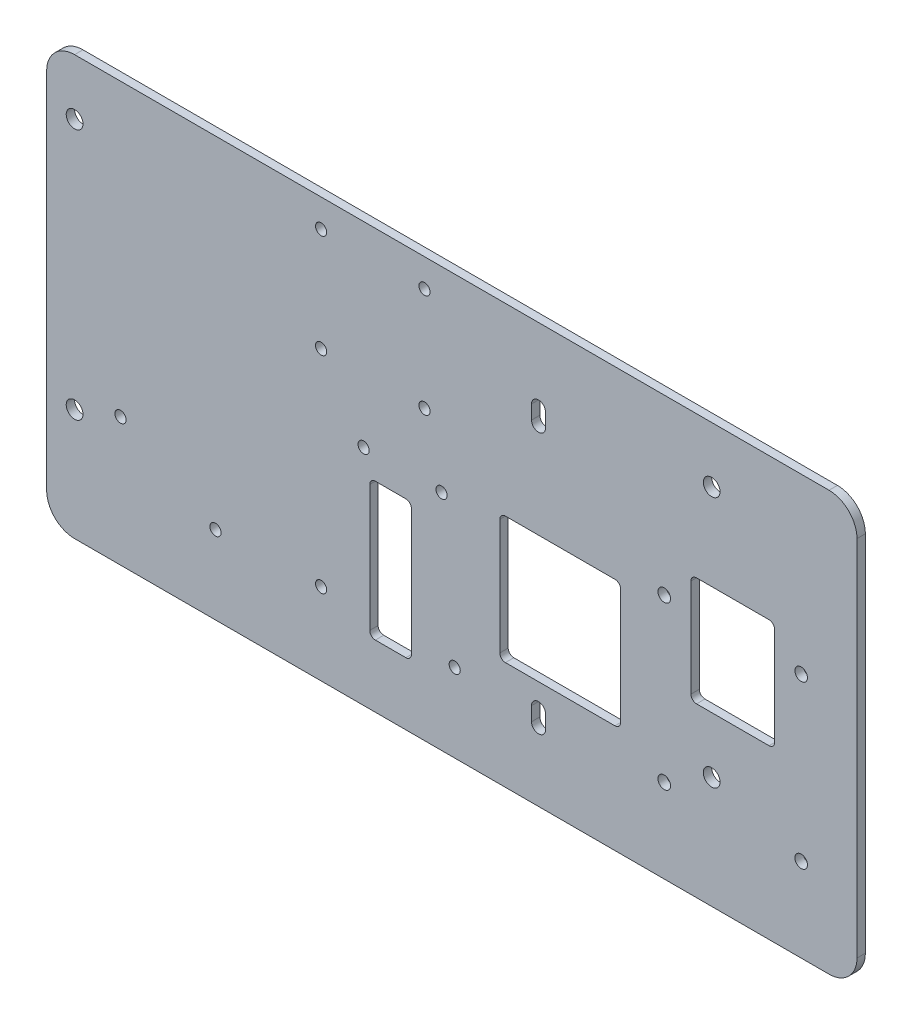
SolidWorks part; units mm, degrees
ref_plane "정면" through (0, 0, 0) normal (0, 0, 1) x (1, 0, 0)
ref_plane "윗면" through (0, 0, 0) normal (0, 1, 0) x (1, 0, 0)
ref_plane "우측면" through (0, 0, 0) normal (1, 0, 0) x (0, 0, -1)
sketch "스케치1" plane through (0, 0, 0) normal (0, 0, 1) x (1, 0, 0)
  line L0 (-145, 65) -> (145, 65) construction
  line L1 (-145, 75) -> (145, 75)
  line L2 (-145, 75) -> (-145, -75)
  line L3 (-145, -75) -> (145, -75)
  line L4 (145, 75) -> (145, -75)
  line L5 (-145, 75) -> (145, -75) construction
  line L6 (-145, -75) -> (145, 75) construction
  line L7 (145, 65) -> (145, 55) construction
  line L8 (145, 55) -> (-145, 55) construction
  line L9 (-145, -65) -> (145, -65) construction
  line L10 (-145, -75) -> (-140, -75)
  line L11 (-145, -75) -> (-145, -55)
  line L12 (-145, -55) -> (-140, -55)
  line L13 (-140, -75) -> (-140, -55)
  line L18 (-125, 55) -> (-145, 25) construction
  line L19 (125, 55) -> (145, 25) construction
  line L20 (31.0272, 46) -> (31.0272, -50) construction
  line L21 (76.0272, 13) -> (125.0272, 13) construction
  line L22 (76.0272, 13) -> (76.0272, -45) construction
  line L23 (76.0272, -45) -> (125.0272, -45) construction
  line L24 (125.0272, 13) -> (125.0272, -45) construction
  line L25 (76.0272, 13) -> (125.0272, -45) construction
  line L26 (76.0272, -45) -> (125.0272, 13) construction
  line L27 (125.0272, -45) -> (161.0272, -45) construction
  line L28 (125.0272, -45) -> (125.0272, 13) construction
  line L29 (125.0272, 13) -> (161.0272, 13) construction
  line L30 (161.0272, -45) -> (161.0272, 13) construction
  line L41 (26.0272, 46) -> (62.0272, 46) construction
  line L42 (26.0272, 46) -> (26.0272, -50) construction
  line L43 (26.0272, -50) -> (62.0272, -50) construction
  line L44 (62.0272, 46) -> (62.0272, -50) construction
  line L45 (26.0272, 46) -> (62.0272, -50) construction
  line L46 (26.0272, -50) -> (62.0272, 46) construction
  line L47 (31.0272, 43.5) -> (31.0272, 48.5) construction
  line L48 (28.5272, 43.5) -> (28.5272, 48.5)
  line L49 (33.5272, 43.5) -> (33.5272, 48.5)
  line L50 (31.0272, -45) -> (31.0272, -50) construction
  line L51 (33.5272, -45) -> (33.5272, -50)
  line L52 (28.5272, -45) -> (28.5272, -50)
  line L53 (-118.5728, -26) -> (-118.5728, -50) construction
  line L54 (-128.3728, -50) -> (-74.7728, -50) construction
  line L55 (-128.3728, -50) -> (-128.3728, -26) construction
  line L56 (-128.3728, -26) -> (-74.7728, -26) construction
  line L57 (-74.7728, -50) -> (-74.7728, -26) construction
  line L58 (-128.3728, -50) -> (-74.7728, -26) construction
  line L59 (-128.3728, -26) -> (-74.7728, -50) construction
  line L60 (-84.5728, -26) -> (-84.5728, -50) construction
  line L61 (-128.3728, -29) -> (-74.7728, -29) construction
  line L62 (-74.7728, -47) -> (-128.3728, -47) construction
  line L63 (-46.7728, 5) -> (1.0272, 5) construction
  line L64 (-46.7728, 5) -> (-46.7728, -46.9) construction
  line L65 (-46.7728, -46.9) -> (1.0272, -46.9) construction
  line L66 (1.0272, 5) -> (1.0272, -46.9) construction
  line L67 (-46.7728, 5) -> (1.0272, -46.9) construction
  line L68 (-46.7728, -46.9) -> (1.0272, 5) construction
  line L69 (1.0272, -46.9) -> (-46.7728, -46.9) construction
  line L70 (1.0272, -46.9) -> (1.0272, -65) construction
  line L71 (1.0272, -65) -> (-46.7728, -65) construction
  line L72 (-46.7728, -46.9) -> (-46.7728, -65) construction
  line L73 (-9.7728, 65) -> (-46.7728, 65) construction
  line L74 (-9.7728, 65) -> (-9.7728, 28) construction
  line L75 (-9.7728, 28) -> (-46.7728, 28) construction
  line L76 (-46.7728, 65) -> (-46.7728, 28) construction
  line L77 (-9.7728, 65) -> (-46.7728, 28) construction
  line L78 (-9.7728, 28) -> (-46.7728, 65) construction
  circle A2 centre (76.0272, 13) radius 2.25
  circle A3 centre (76.0272, -45) radius 2.25
  circle A4 centre (125.0272, -45) radius 2.25
  circle A5 centre (125.0272, 13) radius 2.25
  arc A10 (28.5272, 43.5) -> (33.5272, 43.5) centre (31.0272, 43.5) ccw
  arc A11 (33.5272, 48.5) -> (28.5272, 48.5) centre (31.0272, 48.5) ccw
  arc A12 (33.5272, -45) -> (28.5272, -45) centre (31.0272, -45) ccw
  arc A13 (28.5272, -50) -> (33.5272, -50) centre (31.0272, -50) ccw
  circle A14 centre (-118.5728, -29) radius 2
  circle A15 centre (-84.5728, -47) radius 2
  circle A16 centre (1.0272, -46.9) radius 2
  circle A17 centre (-3.6728, 5) radius 2
  circle A18 centre (-31.5728, 5) radius 2
  circle A19 centre (-46.7728, -45.8) radius 2
  circle A20 centre (-9.7728, 28) radius 2
  circle A21 centre (-46.7728, 28) radius 2
  circle A22 centre (-46.7728, 65) radius 2
  circle A23 centre (-9.7728, 65) radius 2
  point P0 (0, 0)
  point P19 (-22.8729, 49.1702)
  point P20 (100.5272, -14.7878)
  point P21 (0, 0)
  point P26 (100.5272, -16)
  point P38 (-22.8728, -20.95)
  point P49 (44.0272, -2)
  point P60 (31.0272, 46)
  point P66 (31.0272, -47.5)
  point P73 (-101.5728, -38)
  point P89 (-98.5728, -48)
  point P90 (-98.5728, -38.6068)
  point P91 (-98.5728, -38.7528)
  point P92 (-68.0765, -62.8045)
  point P93 (-68.0765, -62.8045)
  point P94 (0, 0)
  point P95 (0, 0)
  point P96 (0, 0)
  point P97 (0, 0)
  point P98 (44.0272, -10.95)
  point P99 (-22.8728, -12)
  point P100 (0, 0)
  point P101 (0, 0)
  point P108 (-28.2728, 46.5)
  dimension "D10" = 25
  dimension "D11" = 50
  dimension "D18" = 51.9
  dimension "D26" = 4
  dimension "D35" = 2.5
  dimension "D36" = 2.5
  dimension "D44" = 4
  dimension "D50" = 4.5
  dimension "D30" = 4
  dimension "D1" = 150
  dimension "D2" = 290
  dimension "D3" = 5
  dimension "D4" = 20
  dimension "D6" = 19.9728
  dimension "D7" = 10
  dimension "D8" = 20
  dimension "D9" = 10
  dimension "D12" = 5
  dimension "D13" = 28
  dimension "D14" = 20
  dimension "D15" = 30
  dimension "D16" = 20
  dimension "D17" = 30
  dimension "D19" = 58
  dimension "D20" = 49
  dimension "D21" = 85
  dimension "D22" = 4.7
  dimension "D23" = 27.9
  dimension "D24" = 15.2
  dimension "D25" = 1.1
  dimension "D27" = 70
  dimension "D28" = 37
  dimension "D29" = 37
  dimension "D31" = 10
  dimension "D32" = 36
  dimension "D33" = 96
  dimension "D34" = 25
  dimension "D37" = 5
  dimension "D38" = 5
  dimension "D39" = 53.6
  dimension "D40" = 24
  dimension "D41" = 34
  dimension "D42" = 18
  dimension "D43" = 3
  dimension "D45" = 17
  dimension "D46" = 30
  dimension "D47" = 10
  dimension "D49" = 25
extrude "보스-돌출1" add sketch "스케치1" against normal blind 3
sketch "스케치5" plane through (0, 0, 0) normal (0, 0, 1) x (1, 0, 0)
  line L0 (93, 75) -> (93, -75) construction
  line L1 (-135, 75) -> (-135, -75) construction
  line L4 (-145, -75) -> (145, -75)
  line L5 (-145, -75) -> (145, -75)
  line L6 (145, 75) -> (-145, 75)
  line L7 (-145, 75) -> (-145, -75)
  line L10 (145, 75) -> (-145, 75)
  line L11 (-145, 75) -> (-145, -75)
  line L14 (145, -75) -> (145, 75)
  line L15 (145, -75) -> (145, 75)
  circle A0 centre (-135, -35) radius 3
  circle A1 centre (-135, 55) radius 3
  circle A2 centre (93, -35) radius 3
  circle A3 centre (93, 55) radius 3
  dimension "D8" = 6
  dimension "D2" = 238
  dimension "D3" = 10
  dimension "D6" = 20
  dimension "D7" = 20
  dimension "D1" = 0
extrude "컷-돌출1" cut sketch "스케치5" against normal blind 10 contours A1 | A0 | A3 | A2
sketch "스케치6" plane through (0, 0, 0) normal (0, 0, 1) x (1, 0, 0)
  line L1 (115.5246, 24.1313) -> (85.5771, 24.1313)
  line L2 (115.5246, 24.1313) -> (115.5246, -14.9169)
  line L3 (115.5246, -14.9169) -> (85.5771, -14.9169)
  line L4 (85.5771, 24.1313) -> (85.5771, -14.9169)
  line L5 (115.5246, 24.1313) -> (85.5771, -14.9169) construction
  line L6 (115.5246, -14.9169) -> (85.5771, 24.1313) construction
  line L7 (60.3966, 9.0768) -> (17.1826, 9.0768)
  line L8 (60.3966, 9.0768) -> (60.3966, -36.3277)
  line L9 (60.3966, -36.3277) -> (17.1826, -36.3277)
  line L10 (17.1826, 9.0768) -> (17.1826, -36.3277)
  line L11 (60.3966, 9.0768) -> (17.1826, -36.3277) construction
  line L12 (60.3966, -36.3277) -> (17.1826, 9.0768) construction
  line L13 (-14.4471, -3.3938) -> (-29.363, -3.3938)
  line L14 (-14.4471, -3.3938) -> (-14.4471, -52.6214)
  line L15 (-14.4471, -52.6214) -> (-29.363, -52.6214)
  line L16 (-29.363, -3.3938) -> (-29.363, -52.6214)
  line L17 (-14.4471, -3.3938) -> (-29.363, -52.6214) construction
  line L18 (-14.4471, -52.6214) -> (-29.363, -3.3938) construction
  point P0 (100.5508, 4.6072)
  point P5 (38.7896, -13.6254)
  point P10 (-21.9051, -28.0076)
  point P15 (38.7896, -13.6254)
  point P16 (100.5508, 4.6072)
extrude "컷-돌출2" cut sketch "스케치6" against normal blind 10
fillet "필렛1" radius 2 12 edges at (-14.4471, -3.3938, -1.5) (-14.4471, -52.6214, -1.5) (-29.363, -52.6214, -1.5) (-29.363, -3.3938, -1.5) (60.3966, 9.0768, -1.5) (17.1826, 9.0768, -1.5) (17.1826, -36.3277, -1.5) (60.3966, -36.3277, -1.5) (115.5246, -14.9169, -1.5) (85.5771, -14.9169, -1.5) (85.5771, 24.1313, -1.5) (115.5246, 24.1313, -1.5)
fillet "필렛2" radius 10 4 edges at (145, -75, -1.5) (145, 75, -1.5) (-145, 75, -1.5) (-145, -75, -1.5)
